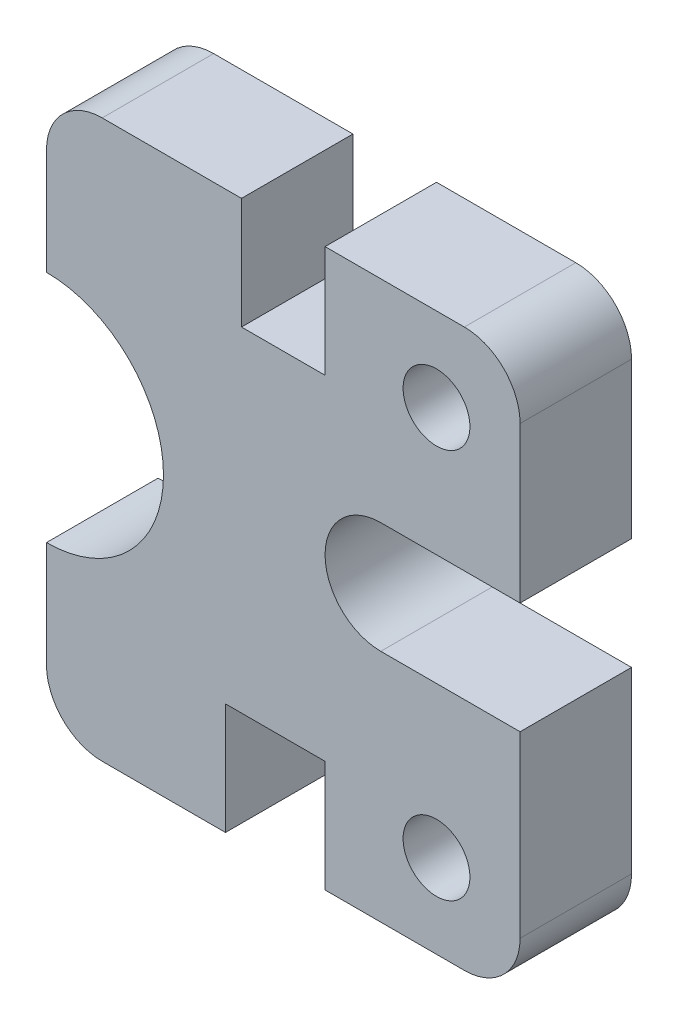
SolidWorks part; units mm, degrees
ref_plane "Front Plane" through (0, 0, 0) normal (0, 0, 1) x (1, 0, 0)
ref_plane "Top Plane" through (0, 0, 0) normal (0, 1, 0) x (1, 0, 0)
ref_plane "Right Plane" through (0, 0, 0) normal (1, 0, 0) x (0, 0, -1)
sketch "Sketch1" plane through (0, 0, 0) normal (0, 0, 1) x (1, 0, 0)
  line L0 (-7.5, 50) -> (-7.5, 30)
  line L1 (-32.5, -50) -> (-10.3726, -50)
  line L2 (-42.5, -40) -> (-42.5, -21)
  line L3 (-32.5, 50) -> (-7.5, 50)
  line L4 (42.5, -40) -> (42.5, -7.9022)
  line L5 (-7.5, 30) -> (7.5, 30)
  line L6 (7.5, 30) -> (7.5, 50)
  line L7 (7.5, -50) -> (7.5, -30)
  line L8 (7.5, -30) -> (-10.3726, -30)
  line L9 (-10.3726, -30) -> (-10.3726, -50)
  line L10 (7.5, 50) -> (32.5, 50)
  line L11 (7.5, -50) -> (32.5, -50)
  line L12 (42.5, 12.0978) -> (17.5, 12.0978)
  line L14 (17.5, -7.9022) -> (42.5, -7.9022)
  line L15 (42.5, 12.0978) -> (42.5, 40)
  line L16 (-42.5, 21) -> (-42.5, 40)
  arc A0 (-42.5, -21) -> (-42.5, 21) centre (-42.5, 0) ccw
  arc A1 (42.5, -40) -> (32.5, -50) centre (32.5, -40) cw
  arc A2 (-32.5, -50) -> (-42.5, -40) centre (-32.5, -40) cw
  arc A3 (-42.5, 40) -> (-32.5, 50) centre (-32.5, 40) cw
  arc A4 (42.5, 40) -> (32.5, 50) centre (32.5, 40) ccw
  arc A5 (17.5, 12.0978) -> (17.5, -7.9022) centre (17.5, 2.0978) ccw
  circle A6 centre (27.5, 35) radius 6
  circle A7 centre (27.5, -35) radius 6
  point P0 (0, 0)
  point P36 (22.4332, 46.4721)
  dimension "D3" = 10
  dimension "D11" = 12
  dimension "D12" = 12
  dimension "D1" = 35
  dimension "D2" = 35
  dimension "D4" = 100
  dimension "D5" = 85
  dimension "D6" = 35
  dimension "D7" = 25
  dimension "D8" = 20
  dimension "D9" = 20
  dimension "D10" = 20
  dimension "D13" = 15
  dimension "D14" = 15
  dimension "D15" = 15
  dimension "D16" = 15
extrude "Boss-Extrude1" add sketch "Sketch1" along normal blind 20
